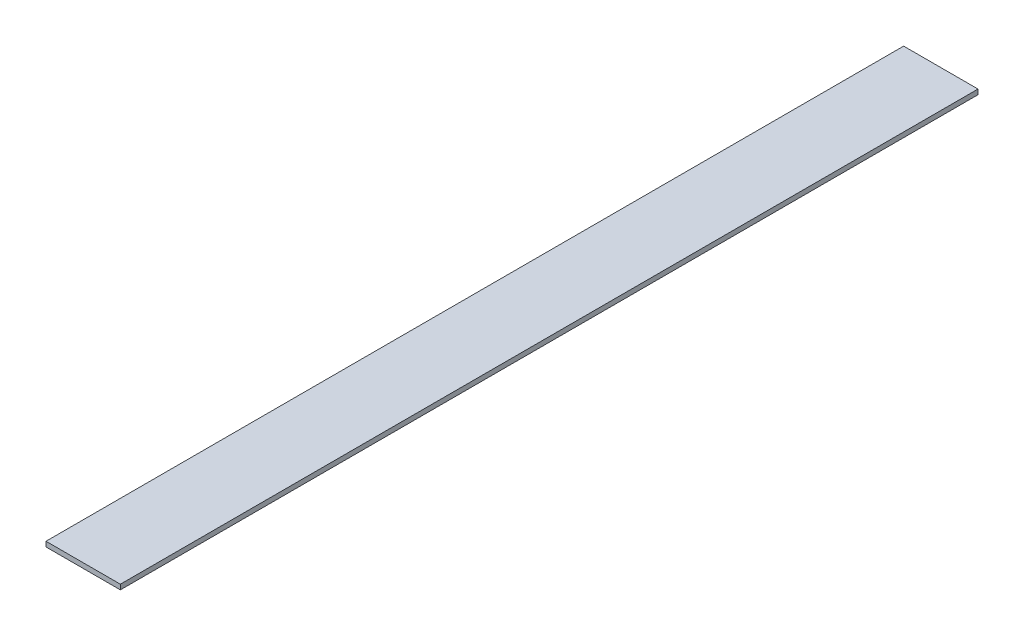
SolidWorks part; units mm, degrees
ref_plane "Front Plane" through (0, 0, 0) normal (0, 0, 1) x (1, 0, 0)
ref_plane "Top Plane" through (0, 0, 0) normal (0, 1, 0) x (1, 0, 0)
ref_plane "Right Plane" through (0, 0, 0) normal (1, 0, 0) x (0, 0, -1)
sketch "Sketch1" plane through (0, 0, 0) normal (0, 0, 1) x (1, 0, 0)
  line L1 (15, -1) -> (-15, -1)
  line L2 (15, -1) -> (15, 1)
  line L3 (15, 1) -> (-15, 1)
  line L4 (-15, -1) -> (-15, 1)
  line L5 (15, -1) -> (-15, 1) construction
  line L6 (15, 1) -> (-15, -1) construction
  point P0 (0, 0)
extrude "Boss-Extrude1" add sketch "Sketch1" along normal blind 200 and the other way up to surface (146 mm away)
